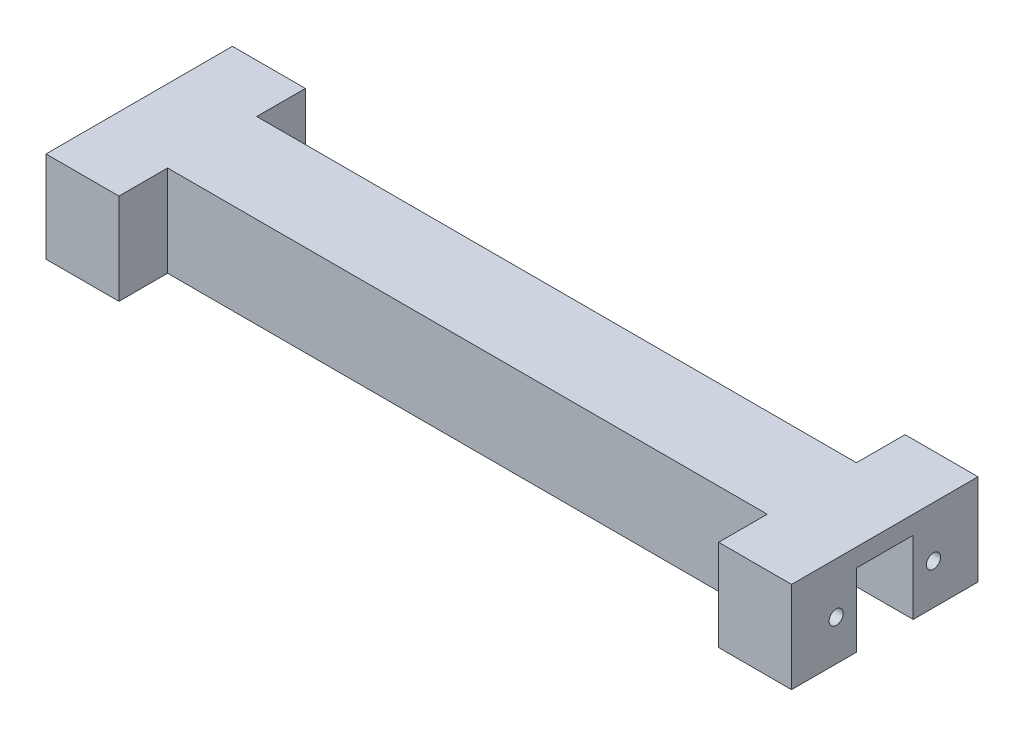
SolidWorks part; units mm, degrees
ref_plane "Front Plane" through (0, 0, 0) normal (0, 0, 1) x (1, 0, 0)
ref_plane "Top Plane" through (0, 0, 0) normal (0, 1, 0) x (1, 0, 0)
ref_plane "Right Plane" through (0, 0, 0) normal (1, 0, 0) x (0, 0, -1)
sketch "Sketch1" plane through (0, 0, 0) normal (0, 1, 0) x (1, 0, 0)
  line L1 (-91.9822, 11) -> (91.9822, 11)
  line L2 (-91.9822, 11) -> (-91.9822, -11)
  line L3 (-91.9822, -11) -> (91.9822, -11)
  line L4 (91.9822, 11) -> (91.9822, -11)
  line L5 (-91.9822, 11) -> (91.9822, -11) construction
  line L6 (-91.9822, -11) -> (91.9822, 11) construction
  point P0 (0, 0)
  dimension "D1" = 183.9644
  dimension "D2" = 22
extrude "Boss-Extrude1" add sketch "Sketch1" along normal blind 22.5
sketch "Sketch2" plane through (0, 0, 0) normal (0, -1, 0) x (1, 0, 0)
  line L7 (-91.9822, -11) -> (-91.9822, 11) construction
  line L10 (-91.9822, -7) -> (91.9822, -7)
  line L16 (-91.9822, -7) -> (-91.9822, 7)
  line L17 (-91.9822, 7) -> (91.9822, 7)
  line L18 (91.9822, -7) -> (91.9822, 7)
  line L19 (91.9822, 11) -> (91.9822, -11) construction
  line L20 (-91.9822, 11) -> (91.9822, 11) construction
  line L21 (91.9822, -11) -> (-91.9822, -11) construction
  point P12 (89, -5.5)
  dimension "D1" = 4
  dimension "D2" = 4
extrude "Cut-Extrude1" cut sketch "Sketch2" against normal blind 18
sketch "Sketch3" plane through (0, 0, 11) normal (0, 0, 1) x (1, 0, 0)
  line L0 (-91.9822, 22.5) -> (91.9822, 22.5) construction
  line L1 (-91.9822, 0) -> (-73.9822, 0)
  line L2 (-91.9822, 0) -> (-91.9822, 22.5)
  line L3 (-91.9822, 22.5) -> (-73.9822, 22.5)
  line L4 (-73.9822, 0) -> (-73.9822, 22.5)
  line L6 (91.9822, 0) -> (73.9822, 0)
  line L7 (91.9822, 0) -> (91.9822, 22.5)
  line L8 (91.9822, 22.5) -> (73.9822, 22.5)
  line L9 (73.9822, 0) -> (73.9822, 22.5)
  dimension "D1" = 18
extrude "Boss-Extrude2" add sketch "Sketch3" along normal blind 12
sketch "Sketch4" plane through (0, 0, -11) normal (0, 0, -1) x (-1, 0, 0)
  line L0 (-91.9822, 22.5) -> (91.9822, 22.5) construction
  line L1 (-91.9822, 0) -> (-73.9822, 0)
  line L2 (-91.9822, 0) -> (-91.9822, 22.5)
  line L3 (-91.9822, 22.5) -> (-73.9822, 22.5)
  line L4 (-73.9822, 0) -> (-73.9822, 22.5)
  line L6 (91.9822, 0) -> (73.9822, 0)
  line L7 (91.9822, 0) -> (91.9822, 22.5)
  line L8 (91.9822, 22.5) -> (73.9822, 22.5)
  line L9 (73.9822, 0) -> (73.9822, 22.5)
  dimension "D1" = 18
extrude "Boss-Extrude3" add sketch "Sketch4" along normal blind 12
sketch "Sketch5" plane through (91.9822, 0, 0) normal (1, 0, 0) x (0, 0, -1)
  line L0 (-7, 18) -> (-7, 0) construction
  line L1 (7, 18) -> (7, 0) construction
  line L2 (-23, 0) -> (-7, 0) construction
  circle A0 centre (-12, 10) radius 1.7526
  circle A1 centre (12, 10) radius 1.7526
  dimension "D1" = 3.5052
  dimension "D2" = 5
  dimension "D3" = 5
  dimension "D4" = 10
extrude "Cut-Extrude2" cut sketch "Sketch5" against normal blind 16
sketch "Sketch6" plane through (-91.9822, 0, 0) normal (-1, 0, 0) x (0, 0, 1)
  line L0 (-23, 0) -> (-7, 0) construction
  line L1 (-7, 18) -> (-7, 0) construction
  line L2 (7, 18) -> (7, 0) construction
  circle A0 centre (-12, 10) radius 1.7526
  circle A1 centre (12, 10) radius 1.7526
  dimension "D2" = 3.5052
  dimension "D3" = 5
  dimension "D1" = 10
  dimension "D4" = 5
extrude "Cut-Extrude3" cut sketch "Sketch6" against normal blind 16
